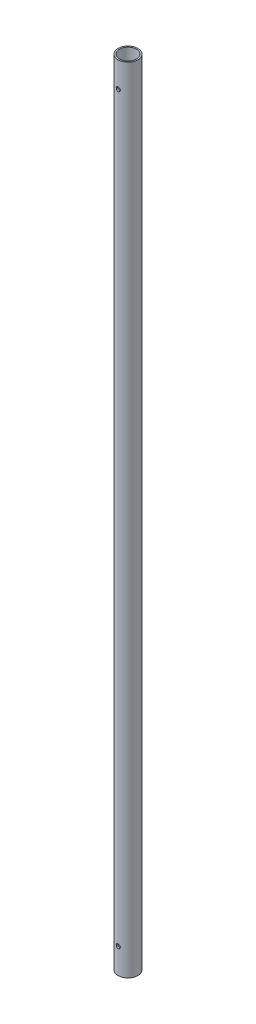
SolidWorks part; units mm, degrees
ref_plane "정면" through (0, 0, 0) normal (0, 0, 1) x (1, 0, 0)
ref_plane "윗면" through (0, 0, 0) normal (0, 1, 0) x (1, 0, 0)
ref_plane "우측면" through (0, 0, 0) normal (1, 0, 0) x (0, 0, -1)
sketch "스케치1" plane through (0, 0, 0) normal (0, 1, 0) x (1, 0, 0)
  circle A2 centre (0, 0) radius 7
  dimension "D1" = 14
extrude "보스-돌출1" add sketch "스케치1" along normal blind 560
sketch "스케치2" plane through (0, 0, 0) normal (0, -1, 0) x (1, 0, 0)
  circle A0 centre (0, 0) radius 6
  dimension "D1" = 12
extrude "컷-돌출1" cut sketch "스케치2" against normal through all both and the other way through all
ref_plane "평면1" through (0, 0, 7) normal (0, 0, 1) x (1, 0, 0)
hole_wizard "M2.5 여유 구멍1" positions "스케치3" profile "스케치4" hole size "M2.5" standard "ISO" end condition through all
sketch "스케치3" plane through (0, 0, 7) normal (0, 0, 1) x (1, 0, 0)
  line L0 (7, 560) -> (-7, 560) construction
  point P0 (0, 18)
  point P5 (0, 542)
  point P9 (0, 0)
  dimension "D1" = 18
  dimension "D2" = 18
sketch "스케치4" plane through (0, 18, 7) normal (1, 0, 0) x (0, -1, 0)
  line L0 (0, 0) -> (0, 14)
  line L1 (0, 14) -> (1.45, 14)
  line L2 (1.45, 14) -> (1.45, 0)
  line L5 (1.45, 0) -> (0, 0)
  line L11 (0, -6.35) -> (0, 107.95) construction
  dimension "관통 구멍 지름" = 2.9
  dimension "관통 구멍 깊이" = 14
